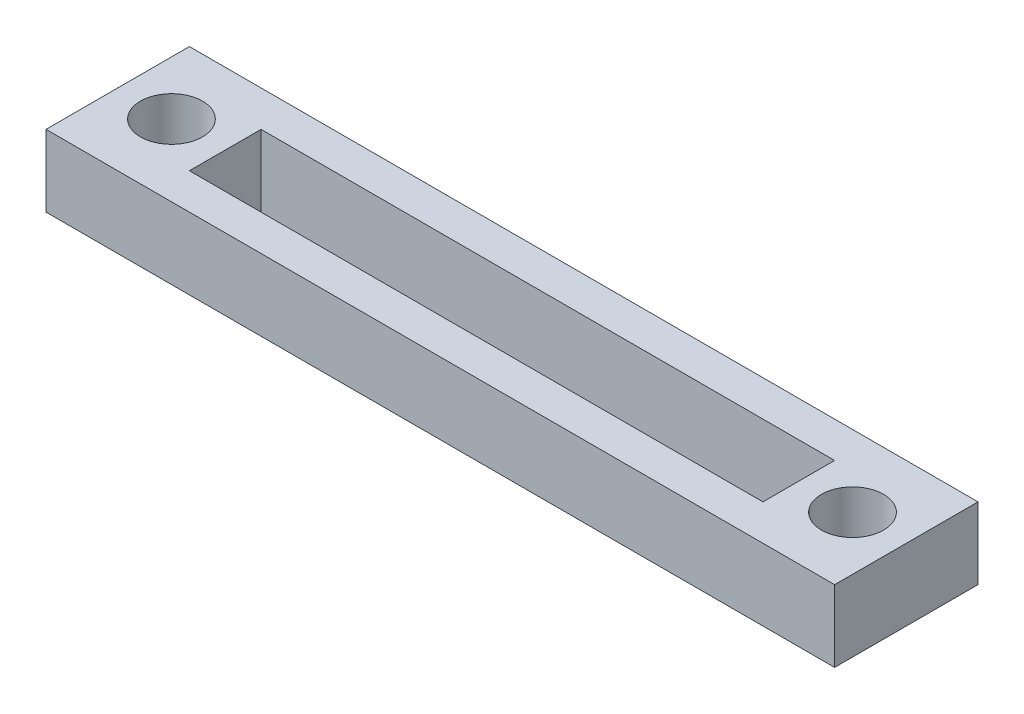
SolidWorks part; units mm, degrees
ref_plane "Front Plane" through (0, 0, 0) normal (0, 0, 1) x (1, 0, 0)
ref_plane "Top Plane" through (0, 0, 0) normal (0, 1, 0) x (1, 0, 0)
ref_plane "Right Plane" through (0, 0, 0) normal (1, 0, 0) x (0, 0, -1)
sketch "Sketch1" plane through (0, 0, 0) normal (0, 1, 0) x (1, 0, 0)
  line L1 (-34.925, -6.35) -> (34.925, -6.35)
  line L2 (-34.925, -6.35) -> (-34.925, 6.35)
  line L3 (-34.925, 6.35) -> (34.925, 6.35)
  line L4 (34.925, -6.35) -> (34.925, 6.35)
  line L5 (-34.925, -6.35) -> (34.925, 6.35) construction
  line L6 (-34.925, 6.35) -> (34.925, -6.35) construction
  line L7 (-25.4, -3.175) -> (25.4, -3.175)
  line L8 (-25.4, -3.175) -> (-25.4, 3.175)
  line L9 (-25.4, 3.175) -> (25.4, 3.175)
  line L10 (25.4, -3.175) -> (25.4, 3.175)
  line L11 (-25.4, -3.175) -> (25.4, 3.175) construction
  line L12 (-25.4, 3.175) -> (25.4, -3.175) construction
  point P0 (0, 0)
  point P6 (0, 0)
  dimension "D1" = 69.85
  dimension "D2" = 6.35
  dimension "D3" = 50.8
  dimension "D4" = 12.7
extrude "Boss-Extrude1" add sketch "Sketch1" along normal blind 6.35
hole_wizard "M5 Clearance Hole1" positions "Sketch2" profile "Sketch3" hole size "M5" standard "ANSI Metric" end condition through all
sketch "Sketch2" plane through (0, 6.35, 0) normal (0, 1, 0) x (1, 0, 0)
  point P9 (-30.1625, 0)
sketch "Sketch3" plane through (-30.1625, 6.35, 0) normal (1, 0, 0) x (0, 0, 1)
  line L0 (0, 0) -> (0, 6.35)
  line L1 (0, 6.35) -> (2.75, 6.35)
  line L2 (2.75, 6.35) -> (2.75, 0)
  line L5 (2.75, 0) -> (0, 0)
  line L11 (0, -6.35) -> (0, 107.95) construction
  dimension "Thru Hole Dia." = 5.5
  dimension "Thru Hole Depth" = 6.35
mirror "Mirror1" about plane through (0, 0, 0) normal (1, 0, 0) of "M5 Clearance Hole1"
